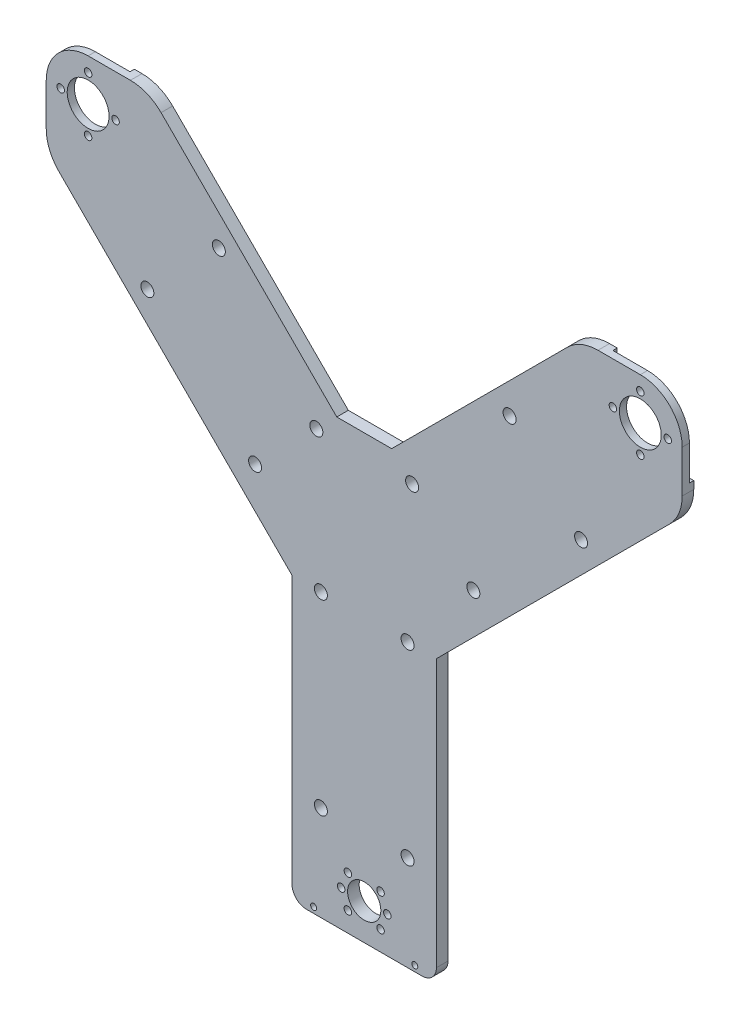
SolidWorks part; units mm, degrees
material "Alliage 1060"
ref_plane "Plan de face" through (0, 0, 0) normal (0, 0, 1) x (1, 0, 0)
ref_plane "Plan de dessus" through (0, 0, 0) normal (0, 1, 0) x (1, 0, 0)
ref_plane "Plan de droite" through (0, 0, 0) normal (1, 0, 0) x (0, 0, -1)
sketch "Esquisse1" plane through (0, 0, 0) normal (0, 0, 1) x (1, 0, 0)
  line L0 (40, -25) -> (-40, -25)
  line L1 (14.8752, -15) -> (-14.8752, -15) construction
  line L2 (-50, -15) -> (-50, 170.2893)
  line L4 (50, -15) -> (50, 170.2893)
  line L5 (220.15, 382.15) -> (220.15, 352.8657)
  line L6 (191.15, 382.15) -> (0, 191) construction
  line L7 (191.15, 382.15) -> (-191.15, 382.15) construction
  line L8 (-191.15, 382.15) -> (0, 191) construction
  line L9 (191.15, 411.15) -> (161.8657, 411.15)
  line L10 (140.6525, 402.3632) -> (19, 280.7107)
  line L11 (211.3632, 331.6525) -> (50, 170.2893)
  line L12 (-191.15, 411.15) -> (-161.8657, 411.15)
  line L13 (-140.6525, 402.3632) -> (-19, 280.7107)
  line L14 (-220.15, 382.15) -> (-220.15, 352.8657)
  line L15 (-211.3632, 331.6525) -> (-50, 170.2893)
  line L16 (-19, 280.7107) -> (19, 280.7107)
  line L17 (0, 0) -> (0, 191) construction
  circle A0 centre (191.15, 382.15) radius 24 construction
  circle A1 centre (191.15, 382.15) radius 24 construction
  circle A2 centre (191.15, 382.15) radius 29
  circle A3 centre (-191.15, 382.15) radius 24 construction
  circle A4 centre (-191.15, 382.15) radius 24 construction
  circle A5 centre (-191.15, 382.15) radius 29
  arc A6 (50, -15) -> (40, -25) centre (40, -15) cw
  arc A7 (-50, -15) -> (-40, -25) centre (-40, -15) ccw
  arc A8 (220.15, 352.8657) -> (211.3632, 331.6525) centre (190.15, 352.8657) cw
  arc A9 (161.8657, 411.15) -> (140.6525, 402.3632) centre (161.8657, 381.15) ccw
  arc A10 (-161.8657, 411.15) -> (-140.6525, 402.3632) centre (-161.8657, 381.15) cw
  arc A11 (-220.15, 352.8657) -> (-211.3632, 331.6525) centre (-190.15, 352.8657) ccw
  point P2 (0, -25)
  point P39 (50, -25)
  point P42 (-50, -25)
  dimension "D12" = 10
  dimension "D13" = 30
  dimension "D1" = 100
  dimension "D2" = 10
  dimension "D3" = 5
  dimension "D4" = 45
  dimension "D5" = 45
  dimension "D7" = 50
  dimension "D8" = 50
  dimension "D9" = 50
  dimension "D10" = 50
  dimension "D11" = 38
  dimension "D6" = 5
extrude "Boss.-Extru.1" add sketch "Esquisse1" against normal blind 4 contours L14 A11 L15 L2 A7 L0 A6 L4 L11 A8 L5 A2 L9 A9 L10 L16 L13 A10 L12 A5 | A2 | A5
sketch "Esquisse4" plane through (0, 0, -4) normal (0, 0, -1) x (-1, 0, 0)
  line L0 (-14.8752, -15) -> (14.8752, -15) construction
  line L1 (14.8752, 15) -> (-14.8752, 15) construction
  line L2 (-14.8752, -15) -> (14.8752, -15)
  line L3 (14.8752, 15) -> (-14.8752, 15)
  line L4 (-191.15, 358.15) -> (-220.15, 358.15)
  line L5 (-220.15, 382.15) -> (-220.15, 352.8657) construction
  line L6 (-167.15, 382.15) -> (-167.15, 411.15)
  line L7 (-191.15, 411.15) -> (-161.8657, 411.15) construction
  line L8 (-191.15, 411.15) -> (-167.15, 411.15)
  line L9 (-220.15, 382.15) -> (-220.15, 358.15)
  line L10 (191.15, 358.15) -> (220.15, 358.15)
  line L11 (220.15, 382.15) -> (220.15, 352.8657) construction
  line L12 (167.15, 382.15) -> (167.15, 411.15)
  line L13 (191.15, 411.15) -> (161.8657, 411.15) construction
  line L14 (191.15, 411.15) -> (167.15, 411.15)
  line L15 (220.15, 382.15) -> (220.15, 358.15)
  arc A0 (14.8752, -15) -> (15.0886, -14.9109) centre (14.8752, -14.7) ccw construction
  arc A1 (-15.0886, -14.9109) -> (-14.8752, -15) centre (-14.8752, -14.7) ccw construction
  arc A2 (-15.0886, 14.9109) -> (-15.0886, -14.9109) centre (0, 0) ccw construction
  arc A3 (-14.8752, 15) -> (-15.0886, 14.9109) centre (-14.8752, 14.7) ccw construction
  arc A4 (15.0886, 14.9109) -> (14.8752, 15) centre (14.8752, 14.7) ccw construction
  arc A5 (15.0886, -14.9109) -> (15.0886, 14.9109) centre (0, 0) ccw construction
  circle A6 centre (-191.15, 382.15) radius 24 construction
  circle A7 centre (191.15, 382.15) radius 24 construction
  arc A8 (14.8752, -15) -> (15.0886, -14.9109) centre (14.8752, -14.7) ccw
  arc A9 (-15.0886, -14.9109) -> (-14.8752, -15) centre (-14.8752, -14.7) ccw
  arc A10 (-15.0886, 14.9109) -> (-15.0886, -14.9109) centre (0, 0) ccw
  arc A11 (-14.8752, 15) -> (-15.0886, 14.9109) centre (-14.8752, 14.7) ccw
  arc A12 (15.0886, 14.9109) -> (14.8752, 15) centre (14.8752, 14.7) ccw
  arc A13 (15.0886, -14.9109) -> (15.0886, 14.9109) centre (0, 0) ccw
  arc A14 (-191.15, 358.15) -> (-167.15, 382.15) centre (-191.15, 382.15) ccw
  arc A15 (167.15, 382.15) -> (191.15, 358.15) centre (191.15, 382.15) ccw
  arc A16 (-191.15, 411.15) -> (-220.15, 382.15) centre (-191.15, 382.15) ccw construction
  arc A17 (-191.15, 411.15) -> (-220.15, 382.15) centre (-191.15, 382.15) ccw
  arc A18 (220.15, 382.15) -> (191.15, 411.15) centre (191.15, 382.15) ccw construction
  arc A19 (220.15, 382.15) -> (191.15, 411.15) centre (191.15, 382.15) ccw
extrude "Enlèv. mat.-Extru.1" cut sketch "Esquisse4" against normal blind 6
sketch "Esquisse7" plane through (0, 0, 0) normal (0, 0, 1) x (1, 0, 0)
  line L0 (220.15, 382.15) -> (220.15, 352.8657) construction
  line L1 (211.3632, 331.6525) -> (50, 170.2893) construction
  line L2 (-220.15, 382.15) -> (-220.15, 352.8657) construction
  line L3 (-211.3632, 331.6525) -> (-50, 170.2893) construction
  line L4 (-50, -15) -> (-50, 170.2893) construction
  line L5 (40, -25) -> (-40, -25) construction
  line L6 (50, -15) -> (50, 170.2893) construction
  line L7 (191.15, 411.15) -> (161.8657, 411.15) construction
  line L8 (140.6525, 402.3632) -> (19, 280.7107) construction
  line L9 (-19, 280.7107) -> (19, 280.7107) construction
  line L10 (-140.6525, 402.3632) -> (-19, 280.7107) construction
  line L11 (-191.15, 411.15) -> (-161.8657, 411.15) construction
  line L12 (220.15, 382.15) -> (220.15, 352.8657)
  line L13 (211.3632, 331.6525) -> (50, 170.2893)
  line L14 (-220.15, 382.15) -> (-220.15, 352.8657)
  line L15 (-211.3632, 331.6525) -> (-50, 170.2893)
  line L16 (-50, -15) -> (-50, 170.2893)
  line L17 (40, -25) -> (-40, -25)
  line L18 (50, -15) -> (50, 170.2893)
  line L19 (191.15, 411.15) -> (161.8657, 411.15)
  line L20 (140.6525, 402.3632) -> (19, 280.7107)
  line L21 (-19, 280.7107) -> (19, 280.7107)
  line L22 (-140.6525, 402.3632) -> (-19, 280.7107)
  line L23 (-191.15, 411.15) -> (-161.8657, 411.15)
  arc A0 (211.3632, 331.6525) -> (220.15, 352.8657) centre (190.15, 352.8657) ccw construction
  circle A1 centre (191.15, 382.15) radius 29
  arc A2 (220.15, 382.15) -> (191.15, 411.15) centre (191.15, 382.15) ccw
  circle A3 centre (-191.15, 382.15) radius 29
  arc A4 (-191.15, 411.15) -> (-220.15, 382.15) centre (-191.15, 382.15) ccw
  arc A5 (-220.15, 352.8657) -> (-211.3632, 331.6525) centre (-190.15, 352.8657) ccw construction
  arc A6 (-50, -15) -> (-40, -25) centre (-40, -15) ccw construction
  arc A7 (40, -25) -> (50, -15) centre (40, -15) ccw construction
  arc A8 (161.8657, 411.15) -> (140.6525, 402.3632) centre (161.8657, 381.15) ccw construction
  arc A9 (-140.6525, 402.3632) -> (-161.8657, 411.15) centre (-161.8657, 381.15) ccw construction
  arc A10 (211.3632, 331.6525) -> (220.15, 352.8657) centre (190.15, 352.8657) ccw
  arc A11 (-220.15, 352.8657) -> (-211.3632, 331.6525) centre (-190.15, 352.8657) ccw
  arc A12 (-50, -15) -> (-40, -25) centre (-40, -15) ccw
  arc A13 (40, -25) -> (50, -15) centre (40, -15) ccw
  arc A14 (161.8657, 411.15) -> (140.6525, 402.3632) centre (161.8657, 381.15) ccw
  arc A15 (-140.6525, 402.3632) -> (-161.8657, 411.15) centre (-161.8657, 381.15) ccw
  dimension "D1" = 0
  dimension "D2" = 0
extrude "Boss.-Extru.3" add sketch "Esquisse7" along normal blind 4
sketch "Esquisse8" plane through (0, 0, -4) normal (0, 0, -1) x (-1, 0, 0)
  circle A0 centre (0, 0) radius 11 construction
  circle A1 centre (0, 0) radius 11
  circle A2 centre (191.15, 382.15) radius 14 construction
  circle A3 centre (-191.15, 382.15) radius 14 construction
  circle A4 centre (191.15, 382.15) radius 14
  circle A5 centre (-191.15, 382.15) radius 14
extrude "Enlèv. mat.-Extru.2" cut sketch "Esquisse8" against normal blind 12
sketch "Esquisse9" plane through (0, 0, -4) normal (0, 0, -1) x (-1, 0, 0)
  line L0 (191.15, 382.15) -> (191.15, 411.15) construction
  line L1 (-191.15, 382.15) -> (-191.15, 411.15) construction
  circle A0 centre (191.15, 382.15) radius 19 construction
  circle A1 centre (-191.15, 382.15) radius 19 construction
  circle A2 centre (191.15, 401.15) radius 2.5
  circle A3 centre (210.15, 382.15) radius 2.5
  circle A4 centre (191.15, 363.15) radius 2.5
  circle A5 centre (172.15, 382.15) radius 2.5
  circle A6 centre (-191.15, 401.15) radius 2.5
  circle A7 centre (-172.15, 382.15) radius 2.5
  circle A8 centre (-191.15, 363.15) radius 2.5
  circle A9 centre (-210.15, 382.15) radius 2.5
  point P18 (191.15, 382.15)
  point P29 (-191.15, 382.15)
  dimension "D1" = 38
  dimension "D2" = 38
  dimension "D3" = 5
  dimension "D5" = 5
  dimension "D4" = 4
  dimension "D6" = 4
extrude "Enlèv. mat.-Extru.3" cut sketch "Esquisse9" against normal blind 20
sketch "Esquisse10" plane through (0, 0, -4) normal (0, 0, -1) x (-1, 0, 0)
  circle A0 centre (-11.3137, 11.3137) radius 2.5 construction
  circle A1 centre (-11.3137, -11.3137) radius 2.5
  circle A2 centre (-11.3137, -11.3137) radius 2.5
  circle A3 centre (16, 0) radius 2.5
  circle A4 centre (16, 0) radius 2.5
  circle A5 centre (11.3137, 11.3137) radius 2.5
  circle A6 centre (11.3137, 11.3137) radius 2.5
  circle A7 centre (-16, 0) radius 2.5
  circle A8 centre (-16, 0) radius 2.5
  circle A9 centre (11.3137, -11.3137) radius 2.5
  circle A10 centre (11.3137, -11.3137) radius 2.5
  circle A11 centre (-11.3137, 11.3137) radius 2.5
  dimension "D1" = 0
  dimension "D2" = 0
  dimension "D3" = 0
  dimension "D4" = 0
  dimension "D5" = 0
extrude "Enlèv. mat.-Extru.4" cut sketch "Esquisse10" against normal blind 12
sketch "Esquisse11" plane through (0, 0, -4) normal (0, 0, -1) x (-1, 0, 0)
  circle A0 centre (30, 40.85) radius 4 construction
  circle A1 centre (-30, 40.85) radius 4 construction
  circle A2 centre (75.5685, 224.1421) radius 4 construction
  circle A3 centre (30, 170.2893) radius 4 construction
  circle A4 centre (-30, 170.2893) radius 4 construction
  circle A5 centre (-75.5685, 224.1421) radius 4 construction
  circle A6 centre (-150.15, 291.6525) radius 4 construction
  circle A7 centre (-100.6525, 341.15) radius 4 construction
  circle A8 centre (-33.1421, 266.5685) radius 4 construction
  circle A9 centre (33.1421, 266.5685) radius 4 construction
  circle A10 centre (100.6525, 341.15) radius 4 construction
  circle A11 centre (150.15, 291.6525) radius 4 construction
  circle A12 centre (30, 40.85) radius 4 construction
  circle A13 centre (-30, 40.85) radius 4 construction
  circle A14 centre (75.5685, 224.1421) radius 4 construction
  circle A15 centre (30, 170.2893) radius 4 construction
  circle A16 centre (-30, 170.2893) radius 4 construction
  circle A17 centre (-75.5685, 224.1421) radius 4 construction
  circle A18 centre (-150.15, 291.6525) radius 4 construction
  circle A19 centre (-100.6525, 341.15) radius 4 construction
  circle A20 centre (-33.1421, 266.5685) radius 4 construction
  circle A21 centre (33.1421, 266.5685) radius 4 construction
  circle A22 centre (100.6525, 341.15) radius 4 construction
  circle A23 centre (150.15, 291.6525) radius 4 construction
  circle A24 centre (100.6525, 341.15) radius 4.5
  circle A25 centre (150.15, 291.6525) radius 4.5
  circle A26 centre (30, 40.85) radius 4.5
  circle A27 centre (-30, 40.85) radius 4.5
  circle A28 centre (75.5685, 224.1421) radius 4.5
  circle A29 centre (30, 170.2893) radius 4.5
  circle A30 centre (-30, 170.2893) radius 4.5
  circle A31 centre (-75.5685, 224.1421) radius 4.5
  circle A32 centre (-33.1421, 266.5685) radius 4.5
  circle A33 centre (33.1421, 266.5685) radius 4.5
  circle A34 centre (-150.15, 291.6525) radius 4.5
  circle A35 centre (-100.6525, 341.15) radius 4.5
  dimension "D1" = 0.5
  dimension "D2" = 0.5
  dimension "D3" = 0.5
extrude "Enlèv. mat.-Extru.5" cut sketch "Esquisse11" against normal blind 14
hole_wizard "Trou taraudé M5x0.81" positions "Esquisse12" profile "Esquisse13" tap size "M5x0.8" standard "Ansi Metric"
sketch "Esquisse12" plane through (0, 0, -4) normal (0, 0, -1) x (-1, 0, 0)
  line L0 (-50, -15) -> (-50, 170.2893) construction
  line L1 (-40, -25) -> (40, -25) construction
  line L2 (50, -15) -> (50, 170.2893) construction
  point P0 (35, -21)
  point P2 (-35, -21)
  dimension "D1" = 15
  dimension "D2" = 4
  dimension "D3" = 15
  dimension "D4" = 4
sketch "Esquisse13" plane through (-35, -21, -4) normal (1, 0, 0) x (0, 1, 0)
  line L0 (0, 0) -> (0, 15.2618)
  line L1 (0, 15.2618) -> (2.1, 14)
  line L2 (2.1, 14) -> (2.1, 0)
  line L5 (2.1, 0) -> (0, 0)
  line L10 (0, 15.2618) -> (-2.1, 14) construction
  line L11 (0, -6.35) -> (0, 107.95) construction
  dimension "Diamètre du trou pour taraudage" = 4.2
  dimension "Profondeur du trou pour taraudage" = 14
  dimension "Angle de pointe" = 118
cosmetic thread "Filetage de perçage1" parameters "D1"=8, "D2"=5
cosmetic thread "Filetage de perçage2" parameters "D1"=8, "D2"=5
sketch "Esquisse14" plane through (0, 0, 0) normal (0, 0, -1) x (-1, 0, 0)
  line L2 (-14.8752, -15) -> (14.8752, -15)
  line L3 (14.8752, 15) -> (-14.8752, 15)
  line L4 (-14.8752, -15) -> (14.8752, -15)
  line L5 (14.8752, 15) -> (-14.8752, 15)
  circle A0 centre (11.3137, -11.3137) radius 2.5 construction
  circle A1 centre (11.3137, -11.3137) radius 2.5
  circle A2 centre (-11.3137, -11.3137) radius 2.5 construction
  circle A3 centre (-16, 0) radius 2.5 construction
  circle A4 centre (-11.3137, 11.3137) radius 2.5 construction
  circle A5 centre (11.3137, 11.3137) radius 2.5 construction
  arc A6 (14.8752, -15) -> (15.0886, -14.9109) centre (14.8752, -14.7) ccw
  arc A7 (15.0886, -14.9109) -> (15.0886, 14.9109) centre (0, 0) ccw
  arc A8 (15.0886, 14.9109) -> (14.8752, 15) centre (14.8752, 14.7) ccw
  arc A9 (-14.8752, 15) -> (-15.0886, 14.9109) centre (-14.8752, 14.7) ccw
  arc A10 (-15.0886, 14.9109) -> (-15.0886, -14.9109) centre (0, 0) ccw
  arc A11 (-15.0886, -14.9109) -> (-14.8752, -15) centre (-14.8752, -14.7) ccw
  arc A12 (14.8752, -15) -> (15.0886, -14.9109) centre (14.8752, -14.7) ccw
  arc A13 (15.0886, -14.9109) -> (15.0886, 14.9109) centre (0, 0) ccw
  arc A14 (15.0886, 14.9109) -> (14.8752, 15) centre (14.8752, 14.7) ccw
  arc A15 (-14.8752, 15) -> (-15.0886, 14.9109) centre (-14.8752, 14.7) ccw
  arc A16 (-15.0886, 14.9109) -> (-15.0886, -14.9109) centre (0, 0) ccw
  arc A17 (-15.0886, -14.9109) -> (-14.8752, -15) centre (-14.8752, -14.7) ccw
  circle A18 centre (16, 0) radius 2.5 construction
  circle A19 centre (-11.3137, -11.3137) radius 2.5
  circle A20 centre (-16, 0) radius 2.5
  circle A21 centre (-11.3137, 11.3137) radius 2.5
  circle A22 centre (11.3137, 11.3137) radius 2.5
  circle A23 centre (16, 0) radius 2.5
  circle A24 centre (0, 0) radius 11 construction
  circle A25 centre (0, 0) radius 11
  dimension "D1" = 0
extrude "Boss.-Extru.4" add sketch "Esquisse14" along normal up to surface (4 mm away) up to face at (-37.1, -21, -4)
sketch "Esquisse15" plane through (0, 0, 0) normal (0, 0, -1) x (-1, 0, 0)
  line L4 (191.15, 411.15) -> (167.15, 411.15)
  line L5 (167.15, 411.15) -> (167.15, 382.15)
  line L6 (191.15, 358.15) -> (220.15, 358.15)
  line L7 (220.15, 358.15) -> (220.15, 382.15)
  line L8 (191.15, 411.15) -> (167.15, 411.15)
  line L9 (167.15, 411.15) -> (167.15, 382.15)
  line L10 (191.15, 358.15) -> (220.15, 358.15)
  line L11 (220.15, 358.15) -> (220.15, 382.15)
  line L12 (-220.15, 382.15) -> (-220.15, 358.15)
  line L13 (-220.15, 358.15) -> (-191.15, 358.15)
  line L14 (-167.15, 382.15) -> (-167.15, 411.15)
  line L15 (-167.15, 411.15) -> (-191.15, 411.15)
  line L16 (-220.15, 382.15) -> (-220.15, 358.15)
  line L17 (-220.15, 358.15) -> (-191.15, 358.15)
  line L18 (-167.15, 382.15) -> (-167.15, 411.15)
  line L19 (-167.15, 411.15) -> (-191.15, 411.15)
  circle A0 centre (172.15, 382.15) radius 2.5 construction
  circle A1 centre (-191.15, 401.15) radius 2.5
  arc A2 (167.15, 382.15) -> (191.15, 358.15) centre (191.15, 382.15) ccw
  arc A3 (220.15, 382.15) -> (191.15, 411.15) centre (191.15, 382.15) ccw
  arc A4 (167.15, 382.15) -> (191.15, 358.15) centre (191.15, 382.15) ccw
  arc A5 (220.15, 382.15) -> (191.15, 411.15) centre (191.15, 382.15) ccw
  circle A6 centre (-191.15, 401.15) radius 2.5
  circle A7 centre (-172.15, 382.15) radius 2.5
  circle A8 centre (-172.15, 382.15) radius 2.5
  circle A9 centre (-191.15, 363.15) radius 2.5
  circle A10 centre (-191.15, 363.15) radius 2.5
  circle A11 centre (-210.15, 382.15) radius 2.5
  circle A12 centre (-210.15, 382.15) radius 2.5
  circle A13 centre (-191.15, 382.15) radius 14
  circle A14 centre (-191.15, 382.15) radius 14
  circle A15 centre (210.15, 382.15) radius 2.5 construction
  circle A16 centre (191.15, 363.15) radius 2.5 construction
  circle A17 centre (191.15, 401.15) radius 2.5 construction
  circle A18 centre (191.15, 382.15) radius 14 construction
  circle A19 centre (172.15, 382.15) radius 2.5
  circle A20 centre (210.15, 382.15) radius 2.5
  circle A21 centre (191.15, 363.15) radius 2.5
  circle A22 centre (191.15, 401.15) radius 2.5
  circle A23 centre (191.15, 382.15) radius 14
  arc A26 (-191.15, 358.15) -> (-167.15, 382.15) centre (-191.15, 382.15) ccw
  arc A27 (-191.15, 411.15) -> (-220.15, 382.15) centre (-191.15, 382.15) ccw
  arc A28 (-191.15, 358.15) -> (-167.15, 382.15) centre (-191.15, 382.15) ccw
  arc A29 (-191.15, 411.15) -> (-220.15, 382.15) centre (-191.15, 382.15) ccw
  dimension "D1" = 0
  dimension "D2" = 0
  dimension "D3" = 0
  dimension "D4" = 0
  dimension "D5" = 0
  dimension "D6" = 0
  dimension "D7" = 0
extrude "Boss.-Extru.5" add sketch "Esquisse15" along normal blind 1
sketch "Esquisse16" plane through (0, 0, -1) normal (0, 0, -1) x (-1, 0, 0)
  circle A0 centre (-191.15, 382.15) radius 14 construction
  circle A1 centre (191.15, 382.15) radius 14 construction
  circle A2 centre (-191.15, 382.15) radius 14
  circle A3 centre (191.15, 382.15) radius 14
  circle A4 centre (-191.15, 382.15) radius 14.5
  circle A5 centre (191.15, 382.15) radius 14.5
  circle A6 centre (-191.15, 363.15) radius 2.5 construction
  circle A7 centre (-172.15, 382.15) radius 2.5 construction
  circle A8 centre (-191.15, 401.15) radius 2.5 construction
  circle A9 centre (-210.15, 382.15) radius 2.5 construction
  circle A10 centre (191.15, 363.15) radius 2.5 construction
  circle A11 centre (210.15, 382.15) radius 2.5 construction
  circle A12 centre (172.15, 382.15) radius 2.5 construction
  circle A13 centre (191.15, 401.15) radius 2.5 construction
  circle A14 centre (-191.15, 363.15) radius 2.5
  circle A15 centre (-172.15, 382.15) radius 2.5
  circle A16 centre (-191.15, 401.15) radius 2.5
  circle A17 centre (-210.15, 382.15) radius 2.5
  circle A18 centre (191.15, 363.15) radius 2.5
  circle A19 centre (210.15, 382.15) radius 2.5
  circle A20 centre (172.15, 382.15) radius 2.5
  circle A21 centre (191.15, 401.15) radius 2.5
  circle A22 centre (-191.15, 401.15) radius 2.6
  circle A23 centre (-172.15, 382.15) radius 2.6
  circle A24 centre (-210.15, 382.15) radius 2.6
  circle A25 centre (-191.15, 363.15) radius 2.6
  circle A26 centre (191.15, 401.15) radius 2.6
  circle A27 centre (210.15, 382.15) radius 2.6
  circle A28 centre (172.15, 382.15) radius 2.6
  circle A29 centre (191.15, 363.15) radius 2.6
  dimension "D1" = 0.5
  dimension "D2" = 0.5
  dimension "D3" = 0.1
extrude "Enlèv. mat.-Extru.6" cut sketch "Esquisse16" against normal blind 10
sketch "Esquisse17" plane through (0, 0, -4) normal (0, 0, -1) x (-1, 0, 0)
  circle A0 centre (0, 0) radius 11 construction
  circle A1 centre (11.3137, -11.3137) radius 2.5 construction
  circle A2 centre (16, 0) radius 2.5 construction
  circle A3 centre (11.3137, 11.3137) radius 2.5 construction
  circle A4 centre (-11.3137, -11.3137) radius 2.5 construction
  circle A5 centre (-16, 0) radius 2.5 construction
  circle A6 centre (-11.3137, 11.3137) radius 2.5 construction
  circle A7 centre (0, 0) radius 11
  circle A8 centre (11.3137, -11.3137) radius 2.5
  circle A9 centre (16, 0) radius 2.5
  circle A10 centre (11.3137, 11.3137) radius 2.5
  circle A11 centre (-11.3137, -11.3137) radius 2.5
  circle A12 centre (-16, 0) radius 2.5
  circle A13 centre (-11.3137, 11.3137) radius 2.5
  circle A14 centre (-11.3137, 11.3137) radius 2.6
  circle A15 centre (-16, 0) radius 2.6
  circle A16 centre (-11.3137, -11.3137) radius 2.6
  circle A17 centre (11.3137, -11.3137) radius 2.6
  circle A18 centre (16, 0) radius 2.6
  circle A19 centre (11.3137, 11.3137) radius 2.6
  circle A20 centre (0, 0) radius 11.5
  dimension "D1" = 0.1
  dimension "D2" = 0.5
extrude "Enlèv. mat.-Extru.7" cut sketch "Esquisse17" against normal blind 10
